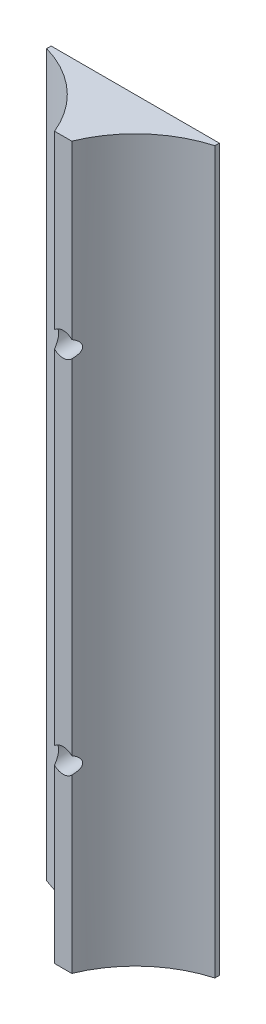
SolidWorks part; units mm, degrees
ref_plane "Front" through (0, 0, 0) normal (0, 0, 1) x (1, 0, 0)
ref_plane "Top" through (0, 0, 0) normal (0, 1, 0) x (1, 0, 0)
ref_plane "Right" through (0, 0, 0) normal (1, 0, 0) x (0, 0, -1)
sketch "Sketch1" plane through (0, 0, 0) normal (0, 1, 0) x (1, 0, 0)
  line L0 (-0.7169, 0) -> (0.7169, 0)
  line L1 (7, 5.629) -> (7, 6)
  line L2 (7, 6) -> (-7, 6)
  line L3 (-7, 6) -> (-7, 5.629)
  arc A0 (0.7169, 0) -> (7, 5.629) centre (9.65, -3.65) cw
  arc A1 (-7, 5.629) -> (-0.7169, 0) centre (-9.65, -3.65) cw
  point P9 (0, 6)
  point P10 (0, 0)
  dimension "D1" = 9.65
  dimension "D6" = 6
  dimension "D2" = 19.3
  dimension "D3" = 9.65
  dimension "D4" = 14
extrude "Boss-Extrude1" add sketch "Sketch1" along normal blind 60
sketch "Sketch3" plane through (0, 0, -6) normal (0, 0, -1) x (-1, 0, 0)
  line L0 (0, 0) -> (0, 60) construction
  line L1 (-7, 0) -> (7, 0) construction
  line L2 (-7, 60) -> (7, 60) construction
  point P6 (0, 45)
  point P7 (0, 15)
  dimension "D1" = 15
  dimension "D2" = 15
hole_wizard "Tapped Hole for M2.5x0.45 Helicoil1" positions "3DSketch1" profile "Sketch4" tap size "M2.5x0.45" standard "Helicoil® Metric"
sketch3d "3DSketch1"
  point P0 (0, 45, -6)
  point P3 (0, 15, -6)
cosmetic thread "Hole Thread1" parameters "D1"=3, "D2"=3.145
cosmetic thread "Hole Thread2" parameters "D1"=3, "D2"=3.145
sketch "Sketch4" plane through (0, 45, -6) normal (1, 0, 0) x (0, 1, 0)
  line L0 (0, 0) -> (0, 4.7661)
  line L1 (0, 4.7661) -> (1.275, 4)
  line L2 (1.275, 4) -> (1.275, 0)
  line L5 (1.275, 0) -> (0, 0)
  line L10 (0, 4.7661) -> (-1.275, 4) construction
  line L11 (0, -6.35) -> (0, 107.95) construction
  dimension "Tap Drill Dia." = 2.55
  dimension "Tap Drill Depth" = 4
  dimension "Drill Angle" = 118
hole_wizard "Ø2.0mm Dowel Hole1" positions "3DSketch2" profile "Sketch5" hole size "Ø2.0" standard "ANSI Metric"
sketch3d "3DSketch2"
  point P0 (0, 45, -6)
  point P3 (0, 15, -6)
sketch "Sketch5" plane through (0, 45, -6) normal (1, 0, 0) x (0, 1, 0)
  line L0 (0, 0) -> (0, 7.0509)
  line L1 (0, 7.0509) -> (1, 6.45)
  line L2 (1, 6.45) -> (1, 0)
  line L5 (1, 0) -> (0, 0)
  line L10 (0, 7.0509) -> (-1, 6.45) construction
  line L11 (0, -6.35) -> (0, 107.95) construction
  dimension "Hole Dia." = 2
  dimension "Hole Depth" = 6.45
  dimension "Drill Angle" = 118
